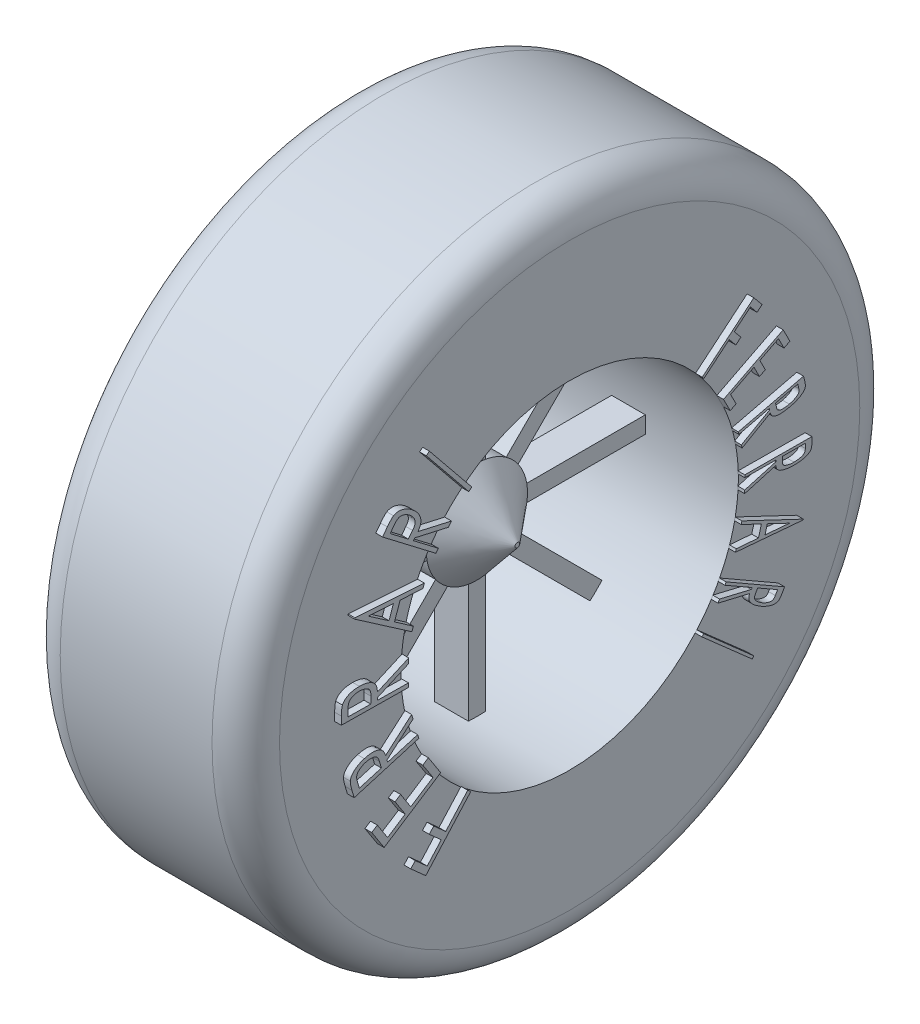
SolidWorks part; units mm, degrees
ref_plane "Front Plane" through (0, 0, 0) normal (0, 0, 1) x (1, 0, 0)
ref_plane "Top Plane" through (0, 0, 0) normal (0, 1, 0) x (1, 0, 0)
ref_plane "Right Plane" through (0, 0, 0) normal (1, 0, 0) x (0, 0, -1)
sketch "Sketch1" plane through (0, 0, 0) normal (0, 0, 1) x (1, 0, 0)
  line L0 (-162.5, 250) -> (-25, 250)
  line L1 (162.5, 250) -> (162.5, 430)
  line L2 (112.5, 480) -> (-112.5, 480)
  line L3 (-162.5, 430) -> (-162.5, 250)
  line L4 (-25, 250) -> (-25, 50)
  line L5 (25, 250) -> (25, 50)
  line L6 (-25, 50) -> (25, 50)
  line L7 (25, 250) -> (162.5, 250)
  line L8 (-90.5883, 0) -> (129.4013, 0) construction
  arc A0 (162.5, 430) -> (112.5, 480) centre (112.5, 430) ccw
  arc A1 (-162.5, 430) -> (-112.5, 480) centre (-112.5, 430) cw
  point P9 (162.5, 480)
  dimension "D4" = 50
  dimension "D1" = 325
  dimension "D2" = 230
  dimension "D3" = 250
  dimension "D5" = 50
  dimension "D7" = 50
revolve "Revolve2" add sketch "Sketch1" angle 360 about L8
sketch "Sketch2" plane through (25, 0, 0) normal (1, 0, 0) x (0, 0, -1)
  line L0 (-12.5, 249.6873) -> (-12.5, 73.951)
  line L1 (12.5, 249.6873) -> (12.5, 73.951)
  line L2 (0, 250) -> (0, 351.4015) construction
  line L3 (167.7168, 185.3944) -> (43.4524, 61.1301)
  line L4 (185.3944, 167.7168) -> (61.1301, 43.4524)
  line L5 (249.6873, 12.5) -> (73.951, 12.5)
  line L6 (249.6873, -12.5) -> (73.951, -12.5)
  line L7 (185.3944, -167.7168) -> (61.1301, -43.4524)
  line L8 (167.7168, -185.3944) -> (43.4524, -61.1301)
  line L9 (12.5, -249.6873) -> (12.5, -73.951)
  line L10 (-12.5, -249.6873) -> (-12.5, -73.951)
  line L11 (-167.7168, -185.3944) -> (-43.4524, -61.1301)
  line L12 (-185.3944, -167.7168) -> (-61.1301, -43.4524)
  line L13 (-249.6873, -12.5) -> (-73.951, -12.5)
  line L14 (-249.6873, 12.5) -> (-73.951, 12.5)
  line L15 (-185.3944, 167.7168) -> (-61.1301, 43.4524)
  line L16 (-167.7168, 185.3944) -> (-43.4524, 61.1301)
  arc A0 (43.4524, 61.1301) -> (12.5, 73.951) centre (0, 0) ccw
  circle A2 centre (0, 0) radius 250 construction
  arc A3 (73.951, 12.5) -> (61.1301, 43.4524) centre (0, 0) ccw
  arc A4 (249.6873, 12.5) -> (185.3944, 167.7168) centre (0, 0) ccw
  arc A5 (61.1301, -43.4524) -> (73.951, -12.5) centre (0, 0) ccw
  arc A6 (185.3944, -167.7168) -> (249.6873, -12.5) centre (0, 0) ccw
  arc A7 (12.5, -73.951) -> (43.4524, -61.1301) centre (0, 0) ccw
  arc A8 (12.5, -249.6873) -> (167.7168, -185.3944) centre (0, 0) ccw
  arc A9 (-43.4524, -61.1301) -> (-12.5, -73.951) centre (0, 0) ccw
  arc A10 (-167.7168, -185.3944) -> (-12.5, -249.6873) centre (0, 0) ccw
  arc A11 (-73.951, -12.5) -> (-61.1301, -43.4524) centre (0, 0) ccw
  arc A13 (-249.6873, -12.5) -> (-185.3944, -167.7168) centre (0, 0) ccw
  arc A14 (-12.5, 249.6873) -> (-167.7168, 185.3944) centre (0, 0) ccw
  arc A15 (-12.5, 73.951) -> (-43.4524, 61.1301) centre (0, 0) ccw
  arc A16 (167.7168, 185.3944) -> (12.5, 249.6873) centre (0, 0) ccw
  arc A17 (-61.1301, 43.4524) -> (-73.951, 12.5) centre (0, 0) ccw
  arc A18 (-185.3944, 167.7168) -> (-249.6873, 12.5) centre (0, 0) ccw
  point P41 (0, 0)
  dimension "D2" = 25
  dimension "D3" = 12.5
  dimension "D4" = 8
extrude "Cut-Extrude1" cut sketch "Sketch2" against normal up to next
sketch "Sketch3" plane through (25, 0, 0) normal (1, 0, 0) x (0, 0, -1)
  circle A0 centre (0, 0) radius 75
extrude "Boss-Extrude1" add sketch "Sketch3" along normal blind 60 draft 50
sketch "Sketch5" plane through (162.5, 0, 0) normal (1, 0, 0) x (0, 0, -1)
  text T0 "FERRARI\r\n" font "Century Gothic" height 100
extrude "Boss-Extrude3" add sketch "Sketch5" along normal blind 10
sketch "Sketch6" plane through (162.5, 0, 0) normal (1, 0, 0) x (0, 0, -1)
  text T0 "FERRARI\r\n" font "Century Gothic" height 100
extrude "Boss-Extrude4" add sketch "Sketch6" along normal blind 10
